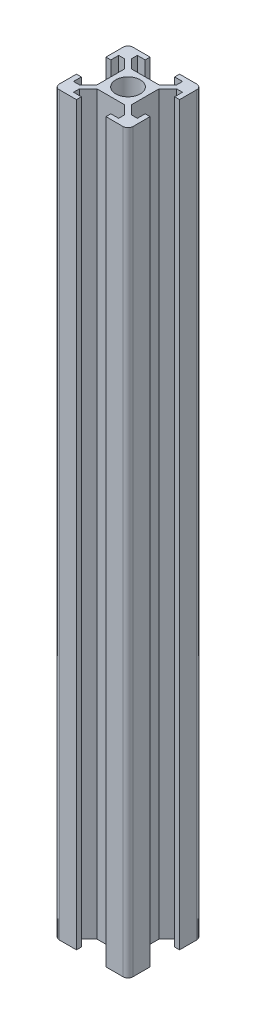
SolidWorks part; units mm, degrees
ref_plane "Front Plane" through (0, 0, 0) normal (0, 0, 1) x (1, 0, 0)
ref_plane "Top Plane" through (0, 0, 0) normal (0, 1, 0) x (1, 0, 0)
ref_plane "Right Plane" through (0, 0, 0) normal (1, 0, 0) x (0, 0, -1)
sketch "Sketch1" plane through (0, 0, 0) normal (0, 1, 0) x (1, 0, 0)
  line L0 (-7.5, -3) -> (-7.5, -6.5)
  line L5 (-6.5, -7.5) -> (-3, -7.5)
  line L6 (-7.5, -3) -> (-6.5, -3)
  line L7 (-3, -7.5) -> (-3, -6.5)
  line L8 (-6.5, -3) -> (-6.5, -4.6)
  line L9 (-3, -6.5) -> (-4.6, -6.5)
  line L10 (-6.5, -4.6) -> (-5.3071, -4.6)
  line L11 (-4.6, -6.5) -> (-4.6, -5.3071)
  line L13 (-3.5071, 0) -> (-3.5071, -2.8)
  line L14 (-3.5071, -2.8) -> (-5.3071, -4.6)
  line L16 (0, -3.5071) -> (-2.8, -3.5071)
  line L17 (-2.8, -3.5071) -> (-4.6, -5.3071)
  line L18 (-3.5071, 2.8) -> (-5.3071, 4.6)
  line L19 (-6.5, 4.6) -> (-5.3071, 4.6)
  line L20 (-6.5, 3) -> (-6.5, 4.6)
  line L21 (-7.5, 3) -> (-6.5, 3)
  line L22 (-7.5, 6.5) -> (-7.5, 3)
  line L23 (-3, 7.5) -> (-6.5, 7.5)
  line L24 (-3, 7.5) -> (-3, 6.5)
  line L25 (-3, 6.5) -> (-4.6, 6.5)
  line L26 (-4.6, 6.5) -> (-4.6, 5.3071)
  line L27 (-2.8, 3.5071) -> (-4.6, 5.3071)
  line L28 (0, 3.5071) -> (-2.8, 3.5071)
  line L31 (-3.5071, 0) -> (-3.5071, 2.8)
  line L32 (2.8, 3.5071) -> (4.6, 5.3071)
  line L33 (4.6, 6.5) -> (4.6, 5.3071)
  line L34 (3, 6.5) -> (4.6, 6.5)
  line L35 (3, 7.5) -> (3, 6.5)
  line L36 (6.5, 7.5) -> (3, 7.5)
  line L37 (7.5, 3) -> (7.5, 6.5)
  line L38 (7.5, 3) -> (6.5, 3)
  line L39 (6.5, 3) -> (6.5, 4.6)
  line L40 (6.5, 4.6) -> (5.3071, 4.6)
  line L41 (3.5071, 2.8) -> (5.3071, 4.6)
  line L42 (3.5071, 0) -> (3.5071, 2.8)
  line L45 (0, 3.5071) -> (2.8, 3.5071)
  line L46 (3.5071, -2.8) -> (5.3071, -4.6)
  line L47 (6.5, -4.6) -> (5.3071, -4.6)
  line L48 (6.5, -3) -> (6.5, -4.6)
  line L49 (7.5, -3) -> (6.5, -3)
  line L50 (7.5, -6.5) -> (7.5, -3)
  line L51 (3, -7.5) -> (6.5, -7.5)
  line L52 (3, -7.5) -> (3, -6.5)
  line L53 (3, -6.5) -> (4.6, -6.5)
  line L54 (4.6, -6.5) -> (4.6, -5.3071)
  line L55 (2.8, -3.5071) -> (4.6, -5.3071)
  line L56 (0, -3.5071) -> (2.8, -3.5071)
  line L59 (3.5071, 0) -> (3.5071, -2.8)
  arc A1 (-6.5, -7.5) -> (-7.5, -6.5) centre (-6.5, -6.5) cw
  arc A2 (-2.5, 0) -> (0, -2.5) centre (0, 0) ccw
  arc A3 (-7.5, 6.5) -> (-6.5, 7.5) centre (-6.5, 6.5) cw
  arc A4 (0, 2.5) -> (-2.5, 0) centre (0, 0) ccw
  arc A5 (6.5, 7.5) -> (7.5, 6.5) centre (6.5, 6.5) cw
  arc A6 (2.5, 0) -> (0, 2.5) centre (0, 0) ccw
  arc A7 (7.5, -6.5) -> (6.5, -7.5) centre (6.5, -6.5) cw
  arc A8 (0, -2.5) -> (2.5, 0) centre (0, 0) ccw
  point P8 (-7.5, -3)
  point P9 (-3, -7.5)
  point P75 (0, 0)
  dimension "D1" = 1
  dimension "D9" = 2.5
  dimension "D2" = 3
  dimension "D3" = 7.5
  dimension "D4" = 3
  dimension "D5" = 1
  dimension "D6" = 1
  dimension "D7" = 1.6
  dimension "D8" = 2.8
  dimension "D10" = 1
  dimension "D11" = 4
extrude "Boss-Extrude1" add sketch "Sketch1" along normal blind 150
